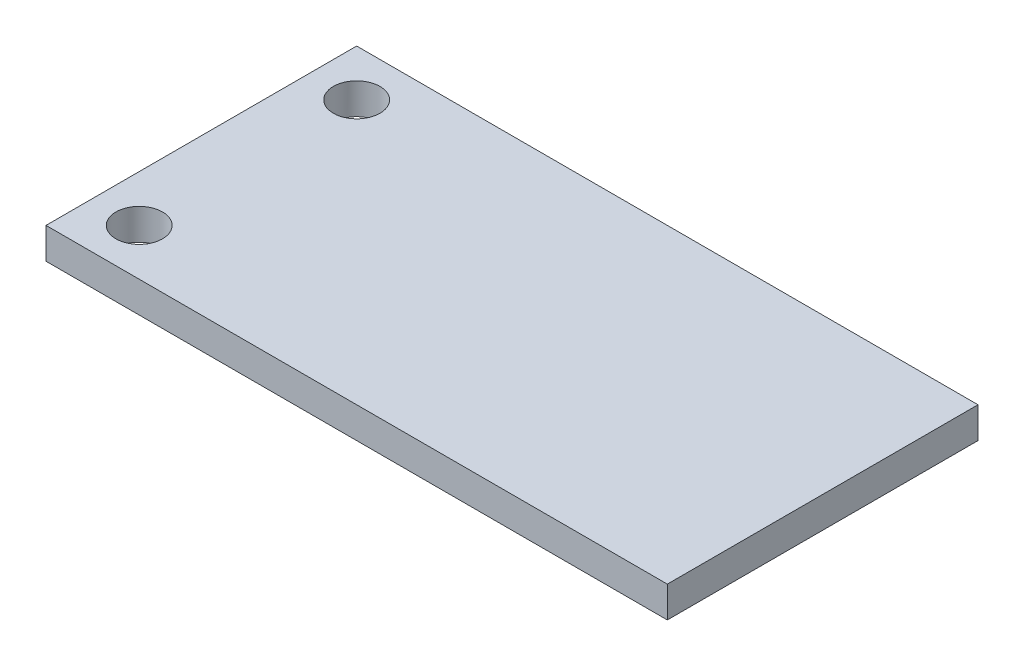
SolidWorks part; units mm, degrees
ref_plane "Front Plane" through (0, 0, 0) normal (0, 0, 1) x (1, 0, 0)
ref_plane "Top Plane" through (0, 0, 0) normal (0, 1, 0) x (1, 0, 0)
ref_plane "Right Plane" through (0, 0, 0) normal (1, 0, 0) x (0, 0, -1)
sketch "Sketch2" plane through (0, 0, 0) normal (0, 1, 0) x (1, 0, 0)
  line L1 (0, 0) -> (40, 0)
  line L2 (0, 0) -> (0, 20)
  line L3 (0, 20) -> (40, 20)
  line L4 (40, 0) -> (40, 20)
  dimension "D1" = 20
  dimension "D2" = 40
extrude "Boss-Extrude1" add sketch "Sketch2" along normal blind 2
sketch "Sketch3" plane through (0, 2, 0) normal (0, 1, 0) x (1, 0, 0)
  line L0 (40, 20) -> (0, 20) construction
  line L1 (0, 20) -> (0, 0) construction
  circle A0 centre (3, 17) radius 1.5
  dimension "D1" = 3
  dimension "D2" = 3
  dimension "D3" = 3
extrude "Cut-Extrude1" cut sketch "Sketch3" against normal up to next
ref_plane "Plane1" through (0, 0, -10) normal (0, 0, -1) x (-1, 0, 0)
mirror "Mirror1" about plane through (0, 0, -10) normal (0, 0, -1) of "Cut-Extrude1"
